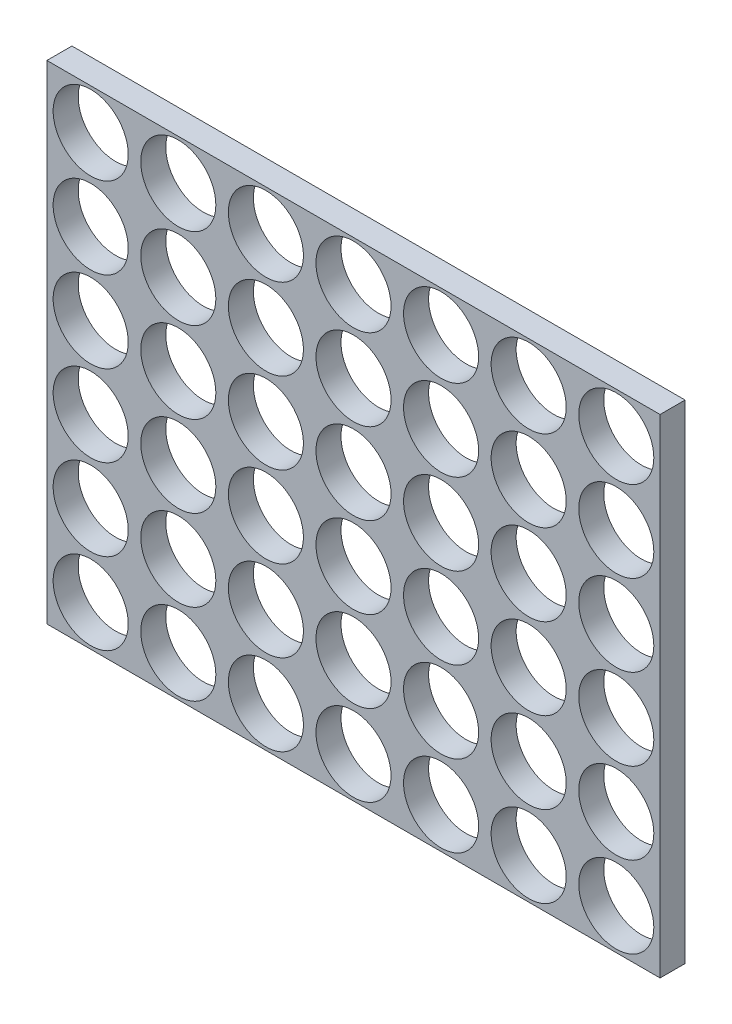
SolidWorks part; units mm, degrees
ref_plane "Ebene vorne" through (0, 0, 0) normal (0, 0, 1) x (1, 0, 0)
ref_plane "Ebene oben" through (0, 0, 0) normal (0, 1, 0) x (1, 0, 0)
ref_plane "Ebene rechts" through (0, 0, 0) normal (1, 0, 0) x (0, 0, -1)
sketch "Sketch1" plane through (0, 0, 0) normal (0, 0, 1) x (1, 0, 0)
  line L1 (122.5, 97.5) -> (-122.5, 97.5)
  line L2 (122.5, 97.5) -> (122.5, -97.5)
  line L3 (122.5, -97.5) -> (-122.5, -97.5)
  line L4 (-122.5, 97.5) -> (-122.5, -97.5)
  line L5 (122.5, 97.5) -> (-122.5, -97.5) construction
  line L6 (122.5, -97.5) -> (-122.5, 97.5) construction
  circle A0 centre (-105, 81.25) radius 15
  circle A1 centre (-70, 81.25) radius 15
  circle A2 centre (-35, 81.25) radius 15
  circle A3 centre (0, 81.25) radius 15
  circle A4 centre (35, 81.25) radius 15
  circle A5 centre (70, 81.25) radius 15
  circle A6 centre (105, 81.25) radius 15
  circle A7 centre (-70, 48.75) radius 15
  circle A8 centre (-35, 48.75) radius 15
  circle A9 centre (0, 48.75) radius 15
  circle A10 centre (35, 48.75) radius 15
  circle A11 centre (70, 48.75) radius 15
  circle A12 centre (105, 48.75) radius 15
  circle A13 centre (-70, 16.25) radius 15
  circle A14 centre (-35, 16.25) radius 15
  circle A15 centre (0, 16.25) radius 15
  circle A16 centre (35, 16.25) radius 15
  circle A17 centre (70, 16.25) radius 15
  circle A18 centre (105, 16.25) radius 15
  circle A19 centre (-70, -16.25) radius 15
  circle A20 centre (-35, -16.25) radius 15
  circle A21 centre (0, -16.25) radius 15
  circle A22 centre (35, -16.25) radius 15
  circle A23 centre (70, -16.25) radius 15
  circle A24 centre (105, -16.25) radius 15
  circle A25 centre (-70, -48.75) radius 15
  circle A26 centre (-35, -48.75) radius 15
  circle A27 centre (0, -48.75) radius 15
  circle A28 centre (35, -48.75) radius 15
  circle A29 centre (70, -48.75) radius 15
  circle A30 centre (105, -48.75) radius 15
  circle A31 centre (-70, -81.25) radius 15
  circle A32 centre (-35, -81.25) radius 15
  circle A33 centre (0, -81.25) radius 15
  circle A34 centre (35, -81.25) radius 15
  circle A35 centre (70, -81.25) radius 15
  circle A36 centre (105, -81.25) radius 15
  circle A37 centre (-105, 48.75) radius 15
  circle A38 centre (-105, 16.25) radius 15
  circle A39 centre (-105, -16.25) radius 15
  circle A40 centre (-105, -48.75) radius 15
  circle A41 centre (-105, -81.25) radius 15
  point P0 (0, 0)
  point P8 (0, 0)
  point P9 (0, 0)
  dimension "D3" = 30
  dimension "D4" = 17.5
  dimension "D5" = 16.25
  dimension "D8" = 32.5
  dimension "D9" = 35
  dimension "D1" = 245
  dimension "D2" = 195
  dimension "D6" = 7
  dimension "D7" = 6
extrude "Boss-Extrude1" add sketch "Sketch1" along normal blind 10
